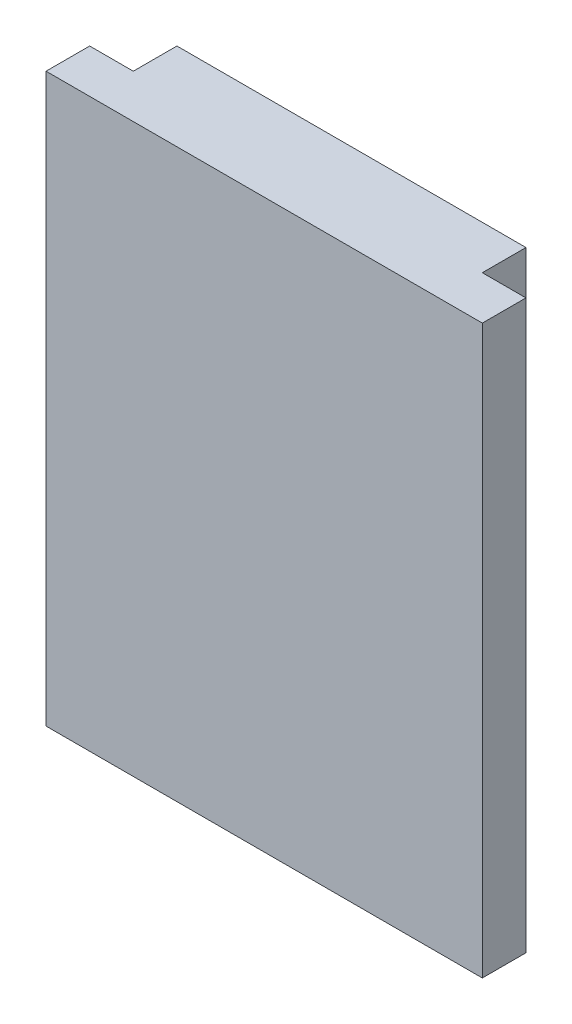
SolidWorks part; units mm, degrees
ref_plane "Plan de face" through (0, 0, 0) normal (0, 0, 1) x (1, 0, 0)
ref_plane "Plan de dessus" through (0, 0, 0) normal (0, 1, 0) x (1, 0, 0)
ref_plane "Plan de droite" through (0, 0, 0) normal (1, 0, 0) x (0, 0, -1)
sketch "Esquisse1" plane through (0, 0, 0) normal (0, 0, 1) x (1, 0, 0)
  line L1 (0, 0) -> (40, 0)
  line L2 (0, 0) -> (0, 65)
  line L3 (0, 65) -> (40, 65)
  line L4 (40, 0) -> (40, 65)
  dimension "D1" = 65
  dimension "D2" = 40
extrude "Boss.-Extru.1" add sketch "Esquisse1" along normal blind 5
sketch "Esquisse2" plane through (0, 0, 5) normal (0, 0, 1) x (1, 0, 0)
  line L0 (20, 0) -> (20, 65) construction
  line L1 (0, 0) -> (40, 0) construction
  line L2 (40, 65) -> (0, 65) construction
  line L3 (40, 0) -> (40, 65) construction
  line L4 (-5, 65) -> (45, 65)
  line L5 (-5, 65) -> (-5, 0)
  line L6 (-5, 0) -> (45, 0)
  line L7 (45, 65) -> (45, 0)
  line L8 (-5, 65) -> (45, 0) construction
  line L9 (-5, 0) -> (45, 65) construction
  point P6 (20, 32.5)
  dimension "D1" = 5
extrude "Boss.-Extru.2" add sketch "Esquisse2" along normal blind 5
